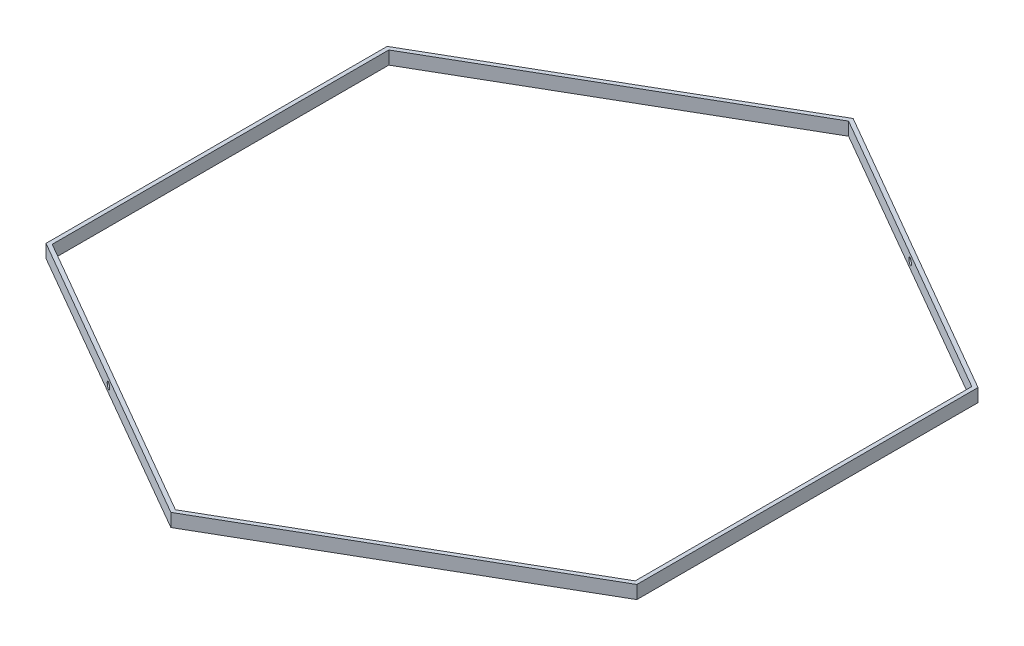
SolidWorks part; units mm, degrees
ref_plane "Plano frontal" through (0, 0, 0) normal (0, 0, 1) x (1, 0, 0)
ref_plane "Plano superior" through (0, 0, 0) normal (0, 1, 0) x (1, 0, 0)
ref_plane "Plano direito" through (0, 0, 0) normal (1, 0, 0) x (0, 0, -1)
sketch "Esboço1" plane through (0, 0, 0) normal (0, 1, 0) x (1, 0, 0)
  line L0 (90, -51.9615) -> (90, 51.9615)
  line L1 (90, 51.9615) -> (0, 103.923)
  line L2 (0, 103.923) -> (-90, 51.9615)
  line L3 (-90, 51.9615) -> (-90, -51.9615)
  line L4 (-90, -51.9615) -> (0, -103.923)
  line L5 (0, -103.923) -> (90, -51.9615)
  line L6 (88.8, 51.2687) -> (0, 102.5374)
  line L7 (0, 102.5374) -> (-88.8, 51.2687)
  line L8 (-88.8, 51.2687) -> (-88.8, -51.2687)
  line L9 (-88.8, -51.2687) -> (0, -102.5374)
  line L10 (0, -102.5374) -> (88.8, -51.2687)
  line L11 (88.8, -51.2687) -> (88.8, 51.2687)
  circle A0 centre (0, 0) radius 90 construction
  dimension "D1" = 180
  dimension "D2" = 1.2
extrude "Ressalto-extrusão1" add sketch "Esboço1" along normal blind 4
sketch "Esboço2" plane through (-45, 0, 77.9423) normal (-0.5, 0, 0.866) x (0.866, 0, 0.5)
  line L0 (-51.9615, 2) -> (0, 2) construction
  line L1 (-51.9615, 4) -> (-51.9615, 0) construction
  line L2 (0, 2) -> (51.9615, 2) construction
  line L3 (51.9615, 4) -> (51.9615, 0) construction
  circle A0 centre (0, 2) radius 1
  dimension "D1" = 2
extrude "Corte-extrusão1" cut sketch "Esboço2" against normal through all
